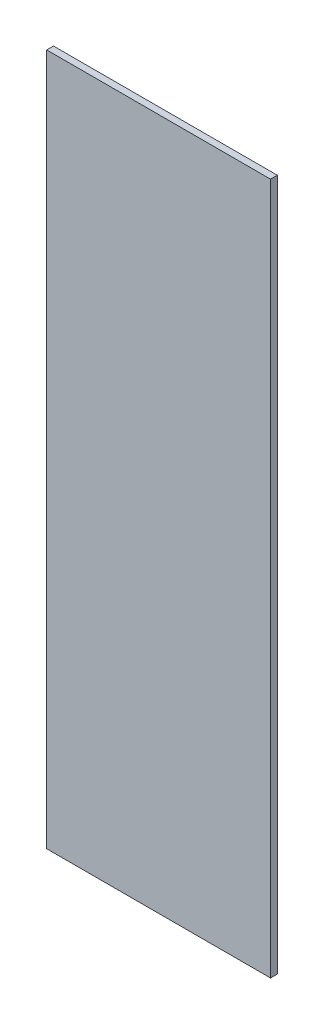
SolidWorks part; units mm, degrees
ref_plane "Front Plane" through (0, 0, 0) normal (0, 0, 1) x (1, 0, 0)
ref_plane "Top Plane" through (0, 0, 0) normal (0, 1, 0) x (1, 0, 0)
ref_plane "Right Plane" through (0, 0, 0) normal (1, 0, 0) x (0, 0, -1)
sketch "Sketch1" plane through (0, 0, 0) normal (0, 0, 1) x (1, 0, 0)
  line L0 (438.7482, -740) -> (1350, -740) construction
  line L1 (438.7482, -180) -> (438.7482, -1300) construction
  line L2 (1350, -765) -> (1350, -715) construction
  line L4 (1350, -230) -> (1020, -230)
  line L5 (1350, -230) -> (1350, -1250)
  line L6 (1350, -1250) -> (1020, -1250)
  line L7 (1020, -230) -> (1020, -1250)
  dimension "D1" = 50
  dimension "D2" = 330
extrude "Boss-Extrude1" add sketch "Sketch1" along normal mid plane 10
